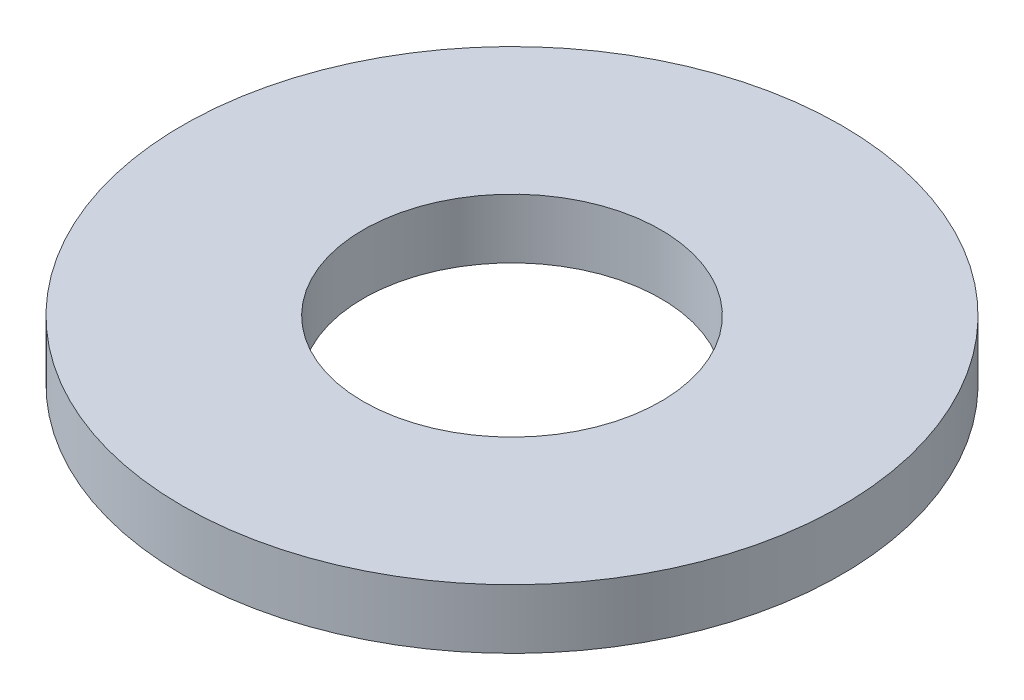
SolidWorks part; units mm, degrees
ref_plane "Front Plane" through (0, 0, 0) normal (0, 0, 1) x (1, 0, 0)
ref_plane "Top Plane" through (0, 0, 0) normal (0, 1, 0) x (1, 0, 0)
ref_plane "Right Plane" through (0, 0, 0) normal (1, 0, 0) x (0, 0, -1)
sketch "Sketch1" plane through (0, 0, 0) normal (0, 1, 0) x (1, 0, 0)
  circle A0 centre (0, 0) radius 11.075
  circle A1 centre (0, 0) radius 5
  dimension "D1" = 22.15
extrude "Boss-Extrude1" add sketch "Sketch1" along normal blind 2
